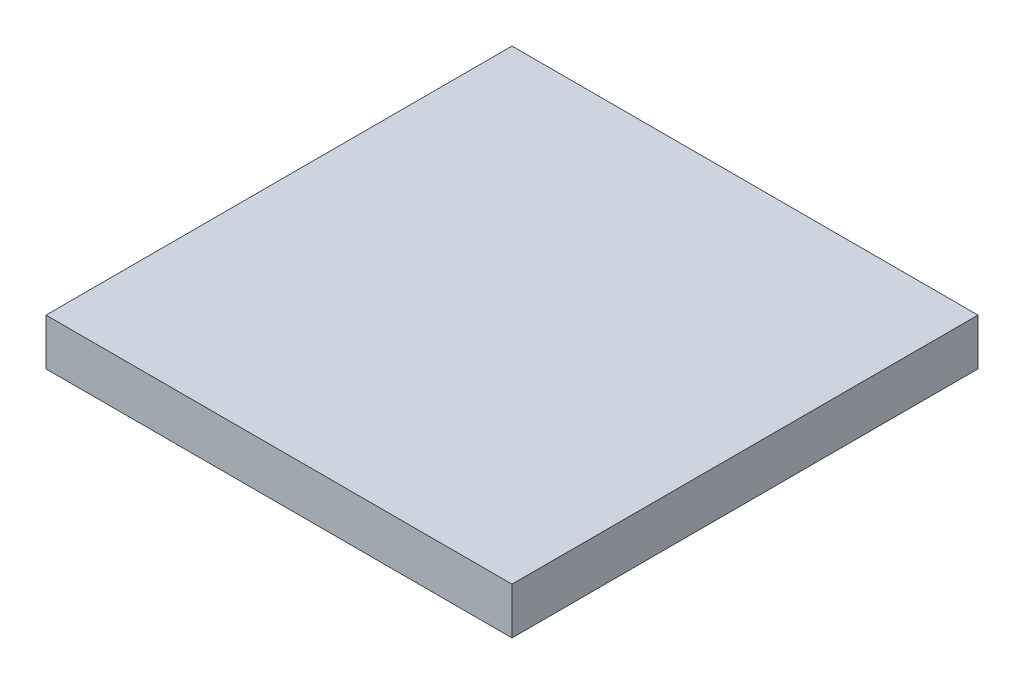
SolidWorks part; units mm, degrees
ref_plane "Front Plane" through (0, 0, 0) normal (0, 0, 1) x (1, 0, 0)
ref_plane "Top Plane" through (0, 0, 0) normal (0, 1, 0) x (1, 0, 0)
ref_plane "Right Plane" through (0, 0, 0) normal (1, 0, 0) x (0, 0, -1)
sketch "Sketch1" plane through (0, 0, 0) normal (0, 1, 0) x (1, 0, 0)
  line L1 (-25.5294, 13.451) -> (-5.5294, 13.451)
  line L2 (-25.5294, 13.451) -> (-25.5294, -6.549)
  line L3 (-25.5294, -6.549) -> (-5.5294, -6.549)
  line L4 (-5.5294, 13.451) -> (-5.5294, -6.549)
  dimension "D1" = 20
  dimension "D2" = 20
extrude "Boss-Extrude1" add sketch "Sketch1" along normal blind 2
